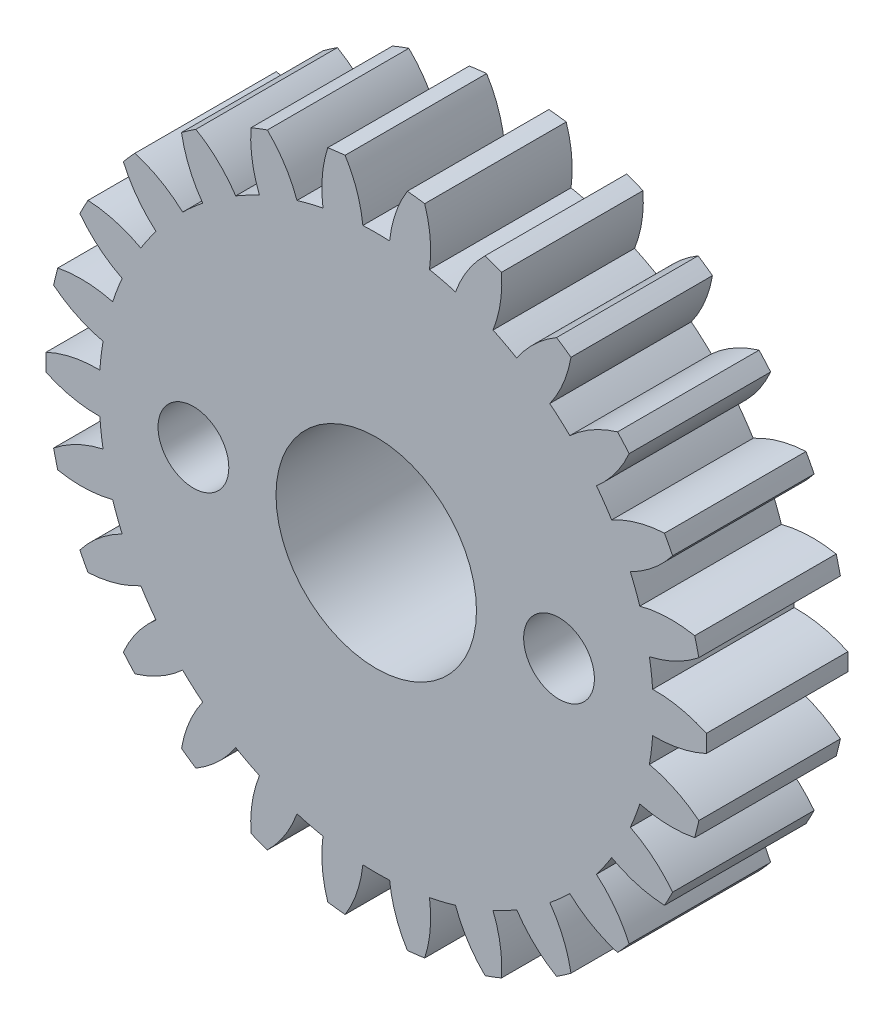
SolidWorks part; units mm, degrees
ref_plane "Alzado" through (0, 0, 0) normal (0, 0, 1) x (1, 0, 0)
ref_plane "Planta" through (0, 0, 0) normal (0, 1, 0) x (1, 0, 0)
ref_plane "Vista lateral" through (0, 0, 0) normal (1, 0, 0) x (0, 0, -1)
sketch "Croquis1" plane through (0, 0, 0) normal (0, 0, 1) x (1, 0, 0)
  circle A0 centre (-25.9111, -0.3998) radius 1.5
  circle A1 centre (-18.1611, -0.3998) radius 4.25
  circle A2 centre (-10.4111, -0.3998) radius 1.5
  arc A3 (-26.4162, 10.9074) -> (-25.5179, 8.7608) centre (-21.2917, 11.7905) ccw
  arc A4 (-25.5179, 8.7608) -> (-26.3681, 8.0076) centre (-18.1611, -0.3998) ccw
  arc A5 (-26.3681, 8.0076) -> (-28.3908, 9.1581) centre (-29.8852, 4.1774) ccw
  arc A6 (-28.3908, 9.1581) -> (-28.8823, 8.6032) centre (-18.1611, -0.3998) ccw
  arc A7 (-28.8823, 8.6032) -> (-27.4964, 6.734) centre (-24.1181, 10.6871) ccw
  arc A8 (-27.4964, 6.734) -> (-28.1416, 5.7992) centre (-18.1611, -0.3998) ccw
  arc A9 (-28.1416, 5.7992) -> (-30.3809, 6.4322) centre (-30.6399, 1.2386) ccw
  arc A10 (-30.3809, 6.4322) -> (-30.7253, 5.7759) centre (-18.1611, -0.3998) ccw
  arc A11 (-30.7253, 5.7759) -> (-28.9324, 4.2926) centre (-26.5983, 8.9393) ccw
  arc A12 (-28.9324, 4.2926) -> (-29.3351, 3.2306) centre (-18.1611, -0.3998) ccw
  arc A13 (-29.3351, 3.2306) -> (-31.6608, 3.3093) centre (-30.6694, -1.7953) ccw
  arc A14 (-31.6608, 3.3093) -> (-31.8382, 2.5896) centre (-18.1611, -0.3998) ccw
  arc A15 (-31.8382, 2.5896) -> (-29.7423, 1.5785) centre (-28.5881, 6.6488) ccw
  arc A16 (-29.7423, 1.5785) -> (-29.8792, 0.4509) centre (-18.1611, -0.3998) ccw
  arc A17 (-29.8792, 0.4509) -> (-32.1562, -0.0292) centre (-29.9719, -4.7482) ccw
  arc A18 (-32.1562, -0.0292) -> (-32.1562, -0.7704) centre (-18.1611, -0.3998) ccw
  arc A19 (-32.1562, -0.7704) -> (-29.8792, -1.2506) centre (-29.9719, 3.9486) ccw
  arc A20 (-29.8792, -1.2506) -> (-29.7423, -2.3781) centre (-18.1611, -0.3998) ccw
  arc A21 (-29.7423, -2.3781) -> (-31.8382, -3.3892) centre (-28.5881, -7.4484) ccw
  arc A22 (-31.8382, -3.3892) -> (-31.6608, -4.1089) centre (-18.1611, -0.3998) ccw
  arc A23 (-31.6608, -4.1089) -> (-29.3351, -4.0302) centre (-30.6694, 0.9957) ccw
  arc A24 (-29.3351, -4.0302) -> (-28.9324, -5.0922) centre (-18.1611, -0.3998) ccw
  arc A25 (-28.9324, -5.0922) -> (-30.7253, -6.5755) centre (-26.5983, -9.7389) ccw
  arc A26 (-30.7253, -6.5755) -> (-30.3809, -7.2318) centre (-18.1611, -0.3998) ccw
  arc A27 (-30.3809, -7.2318) -> (-28.1416, -6.5988) centre (-30.6399, -2.0383) ccw
  arc A28 (-28.1416, -6.5988) -> (-27.4964, -7.5336) centre (-18.1611, -0.3998) ccw
  arc A29 (-27.4964, -7.5336) -> (-28.8823, -9.4029) centre (-24.1181, -11.4867) ccw
  arc A30 (-28.8823, -9.4029) -> (-28.3908, -9.9577) centre (-18.1611, -0.3998) ccw
  arc A31 (-28.3908, -9.9577) -> (-26.3681, -8.8072) centre (-29.8852, -4.977) ccw
  arc A32 (-26.3681, -8.8072) -> (-25.5179, -9.5604) centre (-18.1611, -0.3998) ccw
  arc A33 (-25.5179, -9.5604) -> (-26.4162, -11.707) centre (-21.2917, -12.5902) ccw
  arc A34 (-26.4162, -11.707) -> (-25.8062, -12.1281) centre (-18.1611, -0.3998) ccw
  arc A35 (-25.8062, -12.1281) -> (-24.1176, -10.527) centre (-28.4491, -7.6498) ccw
  arc A36 (-24.1176, -10.527) -> (-23.1119, -11.0548) centre (-18.1611, -0.3998) ccw
  arc A37 (-23.1119, -11.0548) -> (-23.4703, -13.354) centre (-18.2834, -12.9851) ccw
  arc A38 (-23.4703, -13.354) -> (-22.7773, -13.6169) centre (-18.1611, -0.3998) ccw
  arc A39 (-22.7773, -13.6169) -> (-21.5209, -11.6582) centre (-26.4151, -9.9012) ccw
  arc A40 (-21.5209, -11.6582) -> (-20.4181, -11.93) centre (-18.1611, -0.3998) ccw
  arc A41 (-20.4181, -11.93) -> (-20.2159, -14.2482) centre (-15.268, -12.6487) ccw
  arc A42 (-20.2159, -14.2482) -> (-19.4801, -14.3375) centre (-18.1611, -0.3998) ccw
  arc A43 (-19.4801, -14.3375) -> (-18.729, -12.1351) centre (-23.9014, -11.6004) ccw
  arc A44 (-18.729, -12.1351) -> (-17.5932, -12.1351) centre (-18.1611, -0.3998) ccw
  arc A45 (-17.5932, -12.1351) -> (-16.8421, -14.3375) centre (-12.4207, -11.6004) ccw
  arc A46 (-16.8421, -14.3375) -> (-16.1063, -14.2482) centre (-18.1611, -0.3998) ccw
  arc A47 (-16.1063, -14.2482) -> (-15.9041, -11.93) centre (-21.0541, -12.6487) ccw
  arc A48 (-15.9041, -11.93) -> (-14.8012, -11.6582) centre (-18.1611, -0.3998) ccw
  arc A49 (-14.8012, -11.6582) -> (-13.5449, -13.6169) centre (-9.907, -9.9012) ccw
  arc A50 (-13.5449, -13.6169) -> (-12.8518, -13.354) centre (-18.1611, -0.3998) ccw
  arc A51 (-12.8518, -13.354) -> (-13.2103, -11.0548) centre (-18.0387, -12.9851) ccw
  arc A52 (-13.2103, -11.0548) -> (-12.2046, -10.527) centre (-18.1611, -0.3998) ccw
  arc A53 (-12.2046, -10.527) -> (-10.516, -12.1281) centre (-7.8731, -7.6498) ccw
  arc A54 (-10.516, -12.1281) -> (-9.906, -11.707) centre (-18.1611, -0.3998) ccw
  arc A55 (-9.906, -11.707) -> (-10.8042, -9.5604) centre (-15.0304, -12.5902) ccw
  arc A56 (-10.8042, -9.5604) -> (-9.9541, -8.8072) centre (-18.1611, -0.3998) ccw
  arc A57 (-9.9541, -8.8072) -> (-7.9314, -9.9577) centre (-6.437, -4.977) ccw
  arc A58 (-7.9314, -9.9577) -> (-7.4398, -9.4029) centre (-18.1611, -0.3998) ccw
  arc A59 (-7.4398, -9.4029) -> (-8.8258, -7.5336) centre (-12.204, -11.4867) ccw
  arc A60 (-8.8258, -7.5336) -> (-8.1805, -6.5988) centre (-18.1611, -0.3998) ccw
  arc A61 (-8.1805, -6.5988) -> (-5.9413, -7.2318) centre (-5.6823, -2.0383) ccw
  arc A62 (-5.9413, -7.2318) -> (-5.5968, -6.5755) centre (-18.1611, -0.3998) ccw
  arc A63 (-5.5968, -6.5755) -> (-7.3898, -5.0922) centre (-9.7239, -9.7389) ccw
  arc A64 (-7.3898, -5.0922) -> (-6.987, -4.0302) centre (-18.1611, -0.3998) ccw
  arc A65 (-6.987, -4.0302) -> (-4.6613, -4.1089) centre (-5.6528, 0.9957) ccw
  arc A66 (-4.6613, -4.1089) -> (-4.484, -3.3892) centre (-18.1611, -0.3998) ccw
  arc A67 (-4.484, -3.3892) -> (-6.5798, -2.3781) centre (-7.7341, -7.4484) ccw
  arc A68 (-6.5798, -2.3781) -> (-6.4429, -1.2506) centre (-18.1611, -0.3998) ccw
  arc A69 (-6.4429, -1.2506) -> (-4.166, -0.7704) centre (-6.3502, 3.9486) ccw
  arc A70 (-4.166, -0.7704) -> (-4.166, -0.0292) centre (-18.1611, -0.3998) ccw
  arc A71 (-4.166, -0.0292) -> (-6.4429, 0.4509) centre (-6.3502, -4.7482) ccw
  arc A72 (-6.4429, 0.4509) -> (-6.5798, 1.5785) centre (-18.1611, -0.3998) ccw
  arc A73 (-6.5798, 1.5785) -> (-4.484, 2.5896) centre (-7.7341, 6.6488) ccw
  arc A74 (-4.484, 2.5896) -> (-4.6613, 3.3093) centre (-18.1611, -0.3998) ccw
  arc A75 (-4.6613, 3.3093) -> (-6.987, 3.2306) centre (-5.6528, -1.7953) ccw
  arc A76 (-6.987, 3.2306) -> (-7.3898, 4.2926) centre (-18.1611, -0.3998) ccw
  arc A77 (-7.3898, 4.2926) -> (-5.5968, 5.7759) centre (-9.7239, 8.9393) ccw
  arc A78 (-5.5968, 5.7759) -> (-5.9413, 6.4322) centre (-18.1611, -0.3998) ccw
  arc A79 (-5.9413, 6.4322) -> (-8.1805, 5.7992) centre (-5.6823, 1.2386) ccw
  arc A80 (-8.1805, 5.7992) -> (-8.8258, 6.734) centre (-18.1611, -0.3998) ccw
  arc A81 (-8.8258, 6.734) -> (-7.4398, 8.6032) centre (-12.204, 10.6871) ccw
  arc A82 (-7.4398, 8.6032) -> (-7.9314, 9.1581) centre (-18.1611, -0.3998) ccw
  arc A83 (-7.9314, 9.1581) -> (-9.9541, 8.0076) centre (-6.437, 4.1774) ccw
  arc A84 (-9.9541, 8.0076) -> (-10.8042, 8.7608) centre (-18.1611, -0.3998) ccw
  arc A85 (-10.8042, 8.7608) -> (-9.906, 10.9074) centre (-15.0304, 11.7905) ccw
  arc A86 (-9.906, 10.9074) -> (-10.516, 11.3285) centre (-18.1611, -0.3998) ccw
  arc A87 (-10.516, 11.3285) -> (-12.2046, 9.7273) centre (-7.8731, 6.8502) ccw
  arc A88 (-12.2046, 9.7273) -> (-13.2103, 10.2552) centre (-18.1611, -0.3998) ccw
  arc A89 (-13.2103, 10.2552) -> (-12.8518, 12.5544) centre (-18.0387, 12.1855) ccw
  arc A90 (-12.8518, 12.5544) -> (-13.5449, 12.8172) centre (-18.1611, -0.3998) ccw
  arc A91 (-13.5449, 12.8172) -> (-14.8012, 10.8585) centre (-9.907, 9.1016) ccw
  arc A92 (-14.8012, 10.8585) -> (-15.9041, 11.1304) centre (-18.1611, -0.3998) ccw
  arc A93 (-15.9041, 11.1304) -> (-16.1063, 13.4486) centre (-21.0541, 11.8491) ccw
  arc A94 (-16.1063, 13.4486) -> (-16.8421, 13.5379) centre (-18.1611, -0.3998) ccw
  arc A95 (-16.8421, 13.5379) -> (-17.5932, 11.3355) centre (-12.4207, 10.8008) ccw
  arc A96 (-17.5932, 11.3355) -> (-18.729, 11.3355) centre (-18.1611, -0.3998) ccw
  arc A97 (-18.729, 11.3355) -> (-19.4801, 13.5379) centre (-23.9014, 10.8008) ccw
  arc A98 (-19.4801, 13.5379) -> (-20.2159, 13.4486) centre (-18.1611, -0.3998) ccw
  arc A99 (-20.2159, 13.4486) -> (-20.4181, 11.1304) centre (-15.268, 11.8491) ccw
  arc A100 (-20.4181, 11.1304) -> (-21.5209, 10.8585) centre (-18.1611, -0.3998) ccw
  arc A101 (-21.5209, 10.8585) -> (-22.7773, 12.8172) centre (-26.4151, 9.1016) ccw
  arc A102 (-22.7773, 12.8172) -> (-23.4703, 12.5544) centre (-18.1611, -0.3998) ccw
  arc A103 (-23.4703, 12.5544) -> (-23.1119, 10.2552) centre (-18.2834, 12.1855) ccw
  arc A104 (-23.1119, 10.2552) -> (-24.1176, 9.7273) centre (-18.1611, -0.3998) ccw
  arc A105 (-24.1176, 9.7273) -> (-25.8062, 11.3285) centre (-28.4491, 6.8502) ccw
  arc A106 (-25.8062, 11.3285) -> (-26.4162, 10.9074) centre (-18.1611, -0.3998) ccw
  point P26 (-18.1611, -0.3998)
extrude "Saliente-Extruir1" add sketch "Croquis1" along normal blind 6
